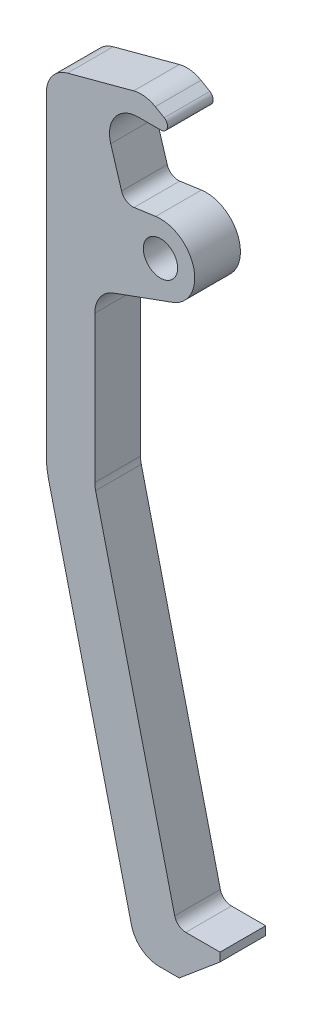
SolidWorks part; units mm, degrees
ref_plane "Plan de face" through (0, 0, 0) normal (0, 0, 1) x (1, 0, 0)
ref_plane "Plan de dessus" through (0, 0, 0) normal (0, 1, 0) x (1, 0, 0)
ref_plane "Plan de droite" through (0, 0, 0) normal (1, 0, 0) x (0, 0, -1)
sketch "Esquisse1" plane through (0, 0, 0) normal (0, 0, 1) x (1, 0, 0)
  line L0 (-4.6227, 5.4113) -> (-0.8319, 5.942)
  line L1 (2.0521, -5.6382) -> (-8.2101, -9.3733)
  line L2 (0, 0) -> (0, 41.2035) construction
  line L3 (-6.8126, 6.8072) -> (-8.713, 13.0232)
  line L4 (-3.9315, 19.4851) -> (0.0685, 19.4851)
  line L5 (0.65, 21.6551) -> (-0.9089, 22.5551)
  line L6 (-4.703, 23.0546) -> (-16.2941, 19.9488)
  line L7 (-20, 15.1192) -> (-20, -39.8808)
  line L8 (-11.5, -14.0718) -> (-11.5, -39.7421)
  line L9 (-19.5839, -43.3893) -> (-5.0821, -103.6695)
  line L10 (-11.3613, -40.9116) -> (2.4852, -98.4678)
  line L11 (-0.2208, -107.5) -> (3.2792, -107.5)
  line L12 (3.2792, -107.5) -> (10.4297, -101.5)
  line L13 (10.4297, -101.5) -> (10.4297, -100)
  line L14 (10.4297, -100) -> (4.4297, -100)
  circle A0 centre (0, 0) radius 3
  arc A1 (-0.8319, 5.942) -> (2.0521, -5.6382) centre (0, 0) cw
  arc A2 (-8.2101, -9.3733) -> (-11.5, -14.0718) centre (-6.5, -14.0718) ccw
  arc A3 (-4.6227, 5.4113) -> (-6.8126, 6.8072) centre (-4.9, 7.392) cw
  arc A4 (-8.713, 13.0232) -> (-3.9315, 19.4851) centre (-3.9315, 14.4851) cw
  arc A5 (0.0685, 19.4851) -> (0.65, 21.6551) centre (0.0685, 20.648) ccw
  arc A6 (-0.9089, 22.5551) -> (-4.703, 23.0546) centre (-3.4089, 18.225) ccw
  arc A7 (-16.2941, 19.9488) -> (-20, 15.1192) centre (-15, 15.1192) ccw
  arc A8 (-20, -39.8808) -> (-19.5839, -43.3893) centre (-5, -39.8808) ccw
  arc A9 (-11.5, -39.7421) -> (-11.3613, -40.9116) centre (-6.5, -39.7421) ccw
  arc A10 (-5.0821, -103.6695) -> (-0.2208, -107.5) centre (-0.2208, -102.5) ccw
  arc A11 (4.4297, -100) -> (2.4852, -98.4678) centre (4.4297, -98) cw
  dimension "D1" = 6
  dimension "D2" = 6
  dimension "D5" = 2
  dimension "D8" = 5
  dimension "D13" = 5
  dimension "D16" = 5
  dimension "D20" = 15
  dimension "D22" = 2
  dimension "D25" = 5
  dimension "D3" = 250
  dimension "D4" = 82.03
  dimension "D6" = 4.9
  dimension "D7" = 17
  dimension "D9" = 4
  dimension "D10" = 6.5
  dimension "D11" = 1.8
  dimension "D12" = 120
  dimension "D14" = 12
  dimension "D15" = 105
  dimension "D17" = 20
  dimension "D18" = 55
  dimension "D19" = 8.5
  dimension "D21" = 6
  dimension "D23" = 100
  dimension "D24" = 62
  dimension "D26" = 3.5
  dimension "D27" = 1.5
  dimension "D28" = 7.5
  dimension "D29" = 40
extrude "Boss.-Extru.1" add sketch "Esquisse1" along normal mid plane 8
equation "\"D16@Esquisse1\"=\"D13@Esquisse1\""
